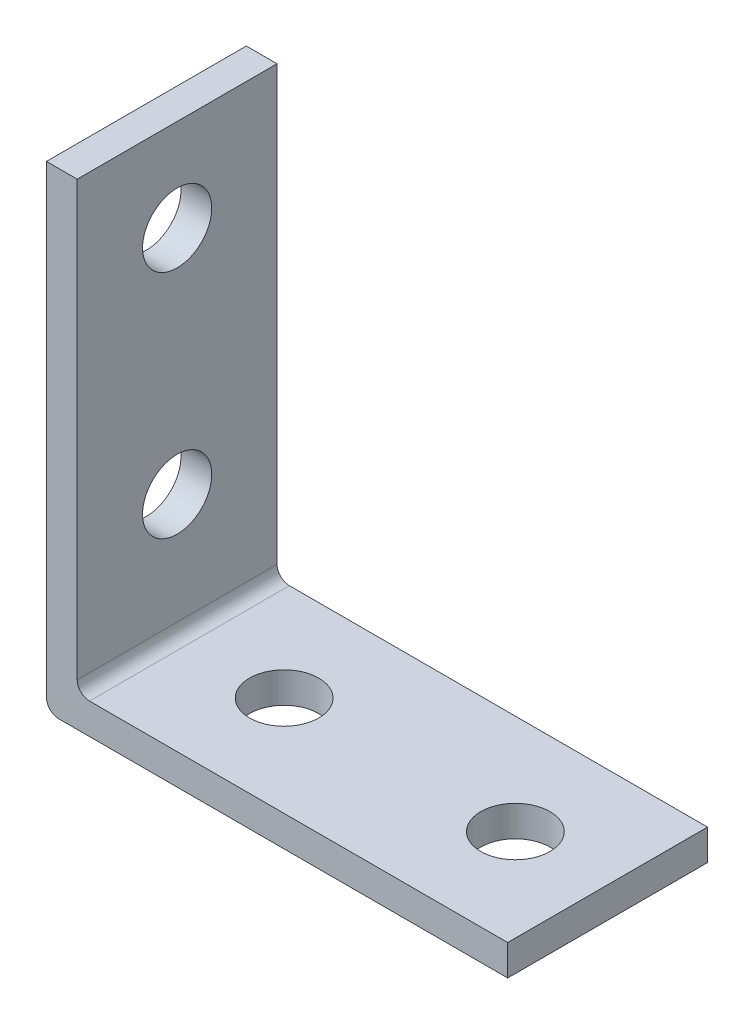
SolidWorks part; units mm, degrees
material "Plain Carbon Steel"
ref_plane "Front Plane" through (0, 0, 0) normal (0, 0, 1) x (1, 0, 0)
ref_plane "Top Plane" through (0, 0, 0) normal (0, 1, 0) x (1, 0, 0)
ref_plane "Right Plane" through (0, 0, 0) normal (1, 0, 0) x (0, 0, -1)
sketch "Sketch1" plane through (0, 0, 0) normal (0, 0, 1) x (1, 0, 0)
  line L1 (-42.2173, 89.9621) -> (-35.8673, 89.9621)
  line L2 (-42.2173, 89.9621) -> (-42.2173, -5.9229)
  line L3 (-39.6773, -8.4629) -> (-35.8673, -8.4629)
  line L4 (-35.8673, 89.9621) -> (-35.8673, 0.4271)
  line L5 (-42.2173, -8.4629) -> (53.0327, -8.4629)
  line L6 (-42.2173, -8.4629) -> (-42.2173, -2.1129)
  line L7 (-33.3273, -2.1129) -> (53.0327, -2.1129)
  line L8 (53.0327, -8.4629) -> (53.0327, -2.1129)
  arc A0 (-33.3273, -2.1129) -> (-35.8673, 0.4271) centre (-33.3273, 0.4271) cw
  arc A1 (-39.6773, -8.4629) -> (-42.2173, -5.9229) centre (-39.6773, -5.9229) cw
  dimension "D5" = 2.54
  dimension "D1" = 98.425
  dimension "D2" = 95.25
  dimension "D3" = 6.35
  dimension "D4" = 6.35
extrude "Boss-Extrude1" add sketch "Sketch1" along normal blind 41.275 contours A1 L3 L5 L8 L7 A0 L4 L1 L2
sketch "Sketch2" plane through (-35.8673, 0, 0) normal (1, 0, 0) x (0, 0, -1)
  line L0 (0, 89.9621) -> (0, 0.4271) construction
  line L1 (-41.275, 89.9621) -> (0, 89.9621) construction
  circle A0 centre (-20.6375, 70.9121) radius 7.1438
  circle A1 centre (-20.6375, 23.2871) radius 7.1438
  dimension "D3" = 14.2875
  dimension "D4" = 14.2875
  dimension "D1" = 20.6375
  dimension "D2" = 20.6375
  dimension "D5" = 19.05
  dimension "D6" = 47.625
extrude "Cut-Extrude1" cut sketch "Sketch2" against normal blind 41.275
sketch "Sketch3" plane through (0, -2.1129, 0) normal (0, 1, 0) x (1, 0, 0)
  line L0 (-33.3273, 0) -> (53.0327, 0) construction
  line L1 (53.0327, -41.275) -> (53.0327, 0) construction
  circle A0 centre (-13.7693, -20.6375) radius 7.1438
  circle A1 centre (33.9827, -20.6375) radius 7.1438
  dimension "D3" = 14.2875
  dimension "D4" = 14.2875
  dimension "D1" = 20.6375
  dimension "D2" = 20.6375
  dimension "D5" = 19.05
  dimension "D6" = 47.752
extrude "Cut-Extrude2" cut sketch "Sketch3" against normal blind 41.275
